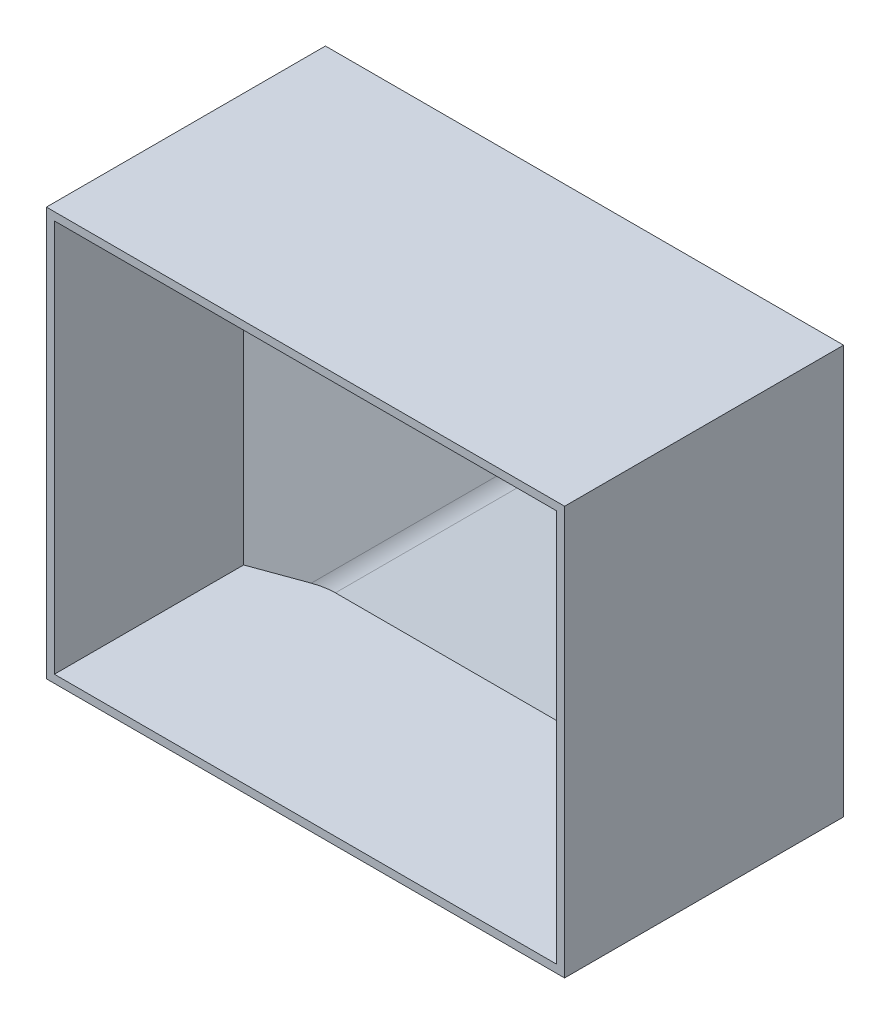
SolidWorks part; units mm, degrees
ref_plane "前视基准面" through (0, 0, 0) normal (0, 0, 1) x (1, 0, 0)
ref_plane "上视基准面" through (0, 0, 0) normal (0, 1, 0) x (1, 0, 0)
ref_plane "右视基准面" through (0, 0, 0) normal (1, 0, 0) x (0, 0, -1)
other "Configuration Table"
sketch "草图1" plane through (0, 0, 0) normal (0, 0, 1) x (1, 0, 0)
  line L1 (-130, 102.5) -> (130, 102.5)
  line L2 (-130, 102.5) -> (-130, -102.5)
  line L3 (-130, -102.5) -> (130, -102.5)
  line L4 (130, 102.5) -> (130, -102.5)
  line L5 (-130, 102.5) -> (130, -102.5) construction
  line L6 (-130, -102.5) -> (130, 102.5) construction
  point P0 (0, 0)
  dimension "D1" = 260
  dimension "D2" = 205
extrude "拉伸-薄壁1" add sketch "草图1" along normal blind 140 thin
sketch "草图2" plane through (0, 0, 0) normal (0, 0, -1) x (-1, 0, 0)
  line L4 (-130, 102.5) -> (-130, -102.5)
  line L5 (-130, -102.5) -> (130, -102.5)
  line L6 (130, -102.5) -> (130, 102.5)
  line L7 (130, 102.5) -> (-130, 102.5)
  line L8 (-130, 102.5) -> (-130, -102.5)
  line L9 (-130, -102.5) -> (130, -102.5)
  line L10 (130, -102.5) -> (130, 102.5)
  line L11 (130, 102.5) -> (-130, 102.5)
  dimension "D1" = 0
extrude "凸台-拉伸1" add sketch "草图2" against normal blind 5
sketch "草图3" plane through (0, 0, 0) normal (0, 0, -1) x (-1, 0, 0)
  circle A0 centre (0, 0) radius 10
  dimension "D1" = 20
extrude "切除-拉伸1" cut sketch "草图3" against normal blind 5
chamfer "倒角1" distance 80 angle 20 2 edges at (0, -98.5, 5) (0, 98.5, 5)
chamfer "倒角2" distance 110 angle 20 2 edges at (-126, 0, 5) (126, 0, 5)
fillet "圆角1" radius 15 4 edges at (-56, -58.5, 19.5588) (-56, 58.5, 19.5588) (56, 58.5, 19.5588) (56, -58.5, 19.5588)
